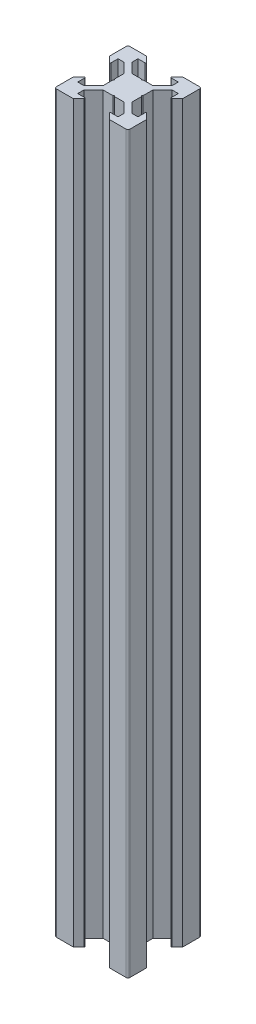
SolidWorks part; units mm, degrees
material "1060 Alloy"
ref_plane "Front Plane" through (0, 0, 0) normal (0, 0, 1) x (1, 0, 0)
ref_plane "Top Plane" through (0, 0, 0) normal (0, 1, 0) x (1, 0, 0)
ref_plane "Right Plane" through (0, 0, 0) normal (1, 0, 0) x (0, 0, -1)
sketch "Sketch1" plane through (0, 0, 0) normal (0, 1, 0) x (1, 0, 0)
  line L0 (-0.2667, -3.9324) -> (-0.0667, -3.7324)
  line L1 (-0.0667, -3.7324) -> (0.1333, -3.9324)
  line L2 (0.1333, -3.9324) -> (2.7733, -3.9324)
  line L3 (2.7733, -3.9324) -> (5.4227, -6.5818)
  line L4 (5.4227, -6.5818) -> (5.4227, -8.2318)
  line L5 (5.4227, -8.2318) -> (3.5162, -8.2318)
  line L6 (3.3748, -8.5732) -> (4.8333, -10.0318)
  line L7 (4.8333, -10.0318) -> (9.4333, -10.0318)
  line L8 (9.9333, -9.5318) -> (9.9333, -4.9318)
  line L9 (9.9333, -4.9318) -> (8.4748, -3.4732)
  line L10 (8.1333, -3.6146) -> (8.1333, -5.5211)
  line L11 (8.1333, -5.5211) -> (6.4833, -5.5211)
  line L12 (6.4833, -5.5211) -> (3.834, -2.8718)
  line L13 (3.834, -2.8718) -> (3.834, -0.2318)
  line L14 (3.834, -0.2318) -> (3.634, -0.0318)
  line L15 (3.634, -0.0318) -> (3.834, 0.1682)
  line L16 (3.834, 0.1682) -> (3.834, 2.8082)
  line L17 (3.834, 2.8082) -> (6.4833, 5.4576)
  line L18 (6.4833, 5.4576) -> (8.1333, 5.4576)
  line L19 (8.1333, 5.4576) -> (8.1333, 3.5511)
  line L20 (8.4748, 3.4096) -> (9.9333, 4.8682)
  line L21 (9.9333, 4.8682) -> (9.9333, 9.4682)
  line L22 (9.4333, 9.9682) -> (4.8333, 9.9682)
  line L23 (4.8333, 9.9682) -> (3.3748, 8.5096)
  line L24 (3.5162, 8.1682) -> (5.4227, 8.1682)
  line L25 (5.4227, 8.1682) -> (5.4227, 6.5182)
  line L26 (5.4227, 6.5182) -> (2.7733, 3.8689)
  line L27 (2.7733, 3.8689) -> (0.1333, 3.8689)
  line L28 (0.1333, 3.8689) -> (-0.0667, 3.6689)
  line L29 (-0.0667, 3.6689) -> (-0.2667, 3.8689)
  line L30 (-0.2667, 3.8689) -> (-2.9067, 3.8689)
  line L31 (-2.9067, 3.8689) -> (-5.556, 6.5182)
  line L32 (-5.556, 6.5182) -> (-5.556, 8.1682)
  line L33 (-5.556, 8.1682) -> (-3.6495, 8.1682)
  line L34 (-3.5081, 8.5096) -> (-4.9667, 9.9682)
  line L35 (-4.9667, 9.9682) -> (-9.5667, 9.9682)
  line L36 (-10.0667, 9.4682) -> (-10.0667, 4.8682)
  line L37 (-10.0667, 4.8682) -> (-8.6081, 3.4096)
  line L38 (-8.2667, 3.5511) -> (-8.2667, 5.4576)
  line L39 (-8.2667, 5.4576) -> (-6.6167, 5.4576)
  line L40 (-6.6167, 5.4576) -> (-3.9673, 2.8082)
  line L41 (-3.9673, 2.8082) -> (-3.9673, 0.1682)
  line L42 (-3.9673, 0.1682) -> (-3.7673, -0.0318)
  line L43 (-3.7673, -0.0318) -> (-3.9673, -0.2318)
  line L44 (-3.9673, -0.2318) -> (-3.9673, -2.8718)
  line L45 (-3.9673, -2.8718) -> (-6.6167, -5.5211)
  line L46 (-6.6167, -5.5211) -> (-8.2667, -5.5211)
  line L47 (-8.2667, -5.5211) -> (-8.2667, -3.6146)
  line L48 (-8.6081, -3.4732) -> (-10.0667, -4.9318)
  line L49 (-10.0667, -4.9318) -> (-10.0667, -9.5318)
  line L50 (-9.5667, -10.0318) -> (-4.9667, -10.0318)
  line L51 (-4.9667, -10.0318) -> (-3.5081, -8.5732)
  line L52 (-3.6495, -8.2318) -> (-5.556, -8.2318)
  line L53 (-5.556, -8.2318) -> (-5.556, -6.5818)
  line L54 (-5.556, -6.5818) -> (-2.9067, -3.9324)
  line L55 (-2.9067, -3.9324) -> (-0.2667, -3.9324)
  line L56 (9.7869, 9.8218) -> (-9.9202, -9.8853) construction
  line L57 (-9.9202, 9.8218) -> (9.7869, -9.8853) construction
  line L58 (-0.0667, 3.6689) -> (-0.0667, -3.7324) construction
  line L60 (-3.7673, -0.0318) -> (3.634, -0.0318) construction
  arc A0 (3.5162, -8.2318) -> (3.3748, -8.5732) centre (3.5162, -8.4318) ccw
  arc A1 (9.4333, -10.0318) -> (9.9333, -9.5318) centre (9.4333, -9.5318) ccw
  arc A2 (8.4748, -3.4732) -> (8.1333, -3.6146) centre (8.3333, -3.6146) ccw
  arc A3 (8.1333, 3.5511) -> (8.4748, 3.4096) centre (8.3333, 3.5511) ccw
  arc A4 (9.9333, 9.4682) -> (9.4333, 9.9682) centre (9.4333, 9.4682) ccw
  arc A5 (3.3748, 8.5096) -> (3.5162, 8.1682) centre (3.5162, 8.3682) ccw
  arc A6 (-3.6495, 8.1682) -> (-3.5081, 8.5096) centre (-3.6495, 8.3682) ccw
  arc A7 (-9.5667, 9.9682) -> (-10.0667, 9.4682) centre (-9.5667, 9.4682) ccw
  arc A8 (-8.6081, 3.4096) -> (-8.2667, 3.5511) centre (-8.4667, 3.5511) ccw
  arc A9 (-8.2667, -3.6146) -> (-8.6081, -3.4732) centre (-8.4667, -3.6146) ccw
  arc A10 (-10.0667, -9.5318) -> (-9.5667, -10.0318) centre (-9.5667, -9.5318) ccw
  arc A11 (-3.5081, -8.5732) -> (-3.6495, -8.2318) centre (-3.6495, -8.4318) ccw
  point P85 (-0.0667, -0.0318)
  point P86 (0, 0)
  point P87 (0, 0)
  point P88 (0, 0)
  point P89 (0, 0)
  point P90 (0, 0)
  point P91 (0, 0)
  dimension "D3" = 0.5
  dimension "D8" = 0.2
  dimension "D1" = 20
  dimension "D2" = 20
  dimension "D4" = 4.6
  dimension "D5" = 2.0627
  dimension "D6" = 1.9065
  dimension "D7" = 1.65
  dimension "D9" = 3.7467
  dimension "D10" = 2.64
extrude "Boss-Extrude1" add sketch "Sketch1" along normal blind 200
